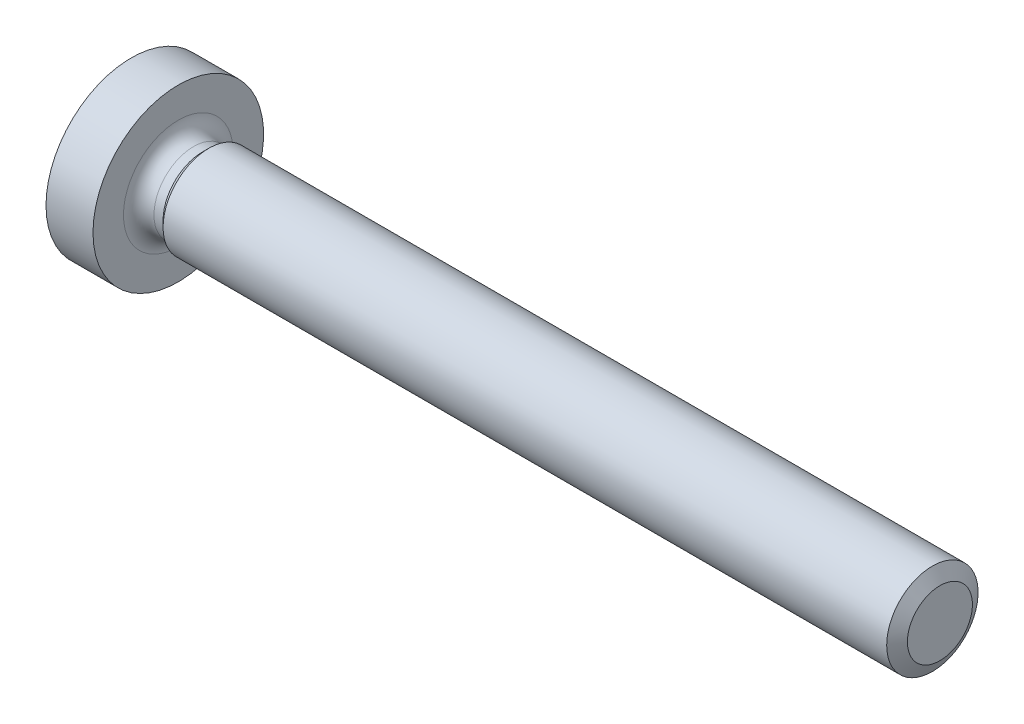
SolidWorks part; units mm, degrees
revolve "基体-旋转" add sketch "草图2" angle 360 about L0
sketch "草图2" plane through (0, 0, 0) normal (0, 0, 1) x (1, 0, 0)
  line L0 (-1.3318, 0) -> (6.5885, 0) construction
  line L1 (0, 0) -> (27.4, 0)
  line L2 (27.4, 0) -> (27.4, 1.5)
  line L3 (27.4, 1.5) -> (3.4, 1.5)
  line L4 (3.4, 1.5) -> (3.199, 1.299)
  line L5 (3.199, 1.299) -> (2.901, 1.299)
  line L6 (2.4, 1.8) -> (2.4, 2.8)
  line L7 (2.4, 2.8) -> (0.8575, 2.8)
  arc A0 (2.4, 1.8) -> (2.901, 1.299) centre (2.901, 1.8) ccw
  arc A1 (0, 0) -> (0.8575, 2.8) centre (5, 0) cw
  dimension "D3" = 5
  dimension "dk" = 5.6
  dimension "d" = 3
  dimension "l" = 25
  dimension "a" = 1
  dimension "D1" = 45
  dimension "D2" = 2.598
  dimension "da" = 3.6
  dimension "k" = 2.4
cosmetic thread "装饰螺纹线1" parameters "D1"=24, "D2"=2.598
ref_plane "前视" through (0, 0, 0) normal (0, 0, 1) x (1, 0, 0)
ref_plane "上视" through (0, 0, 0) normal (0, 1, 0) x (1, 0, 0)
ref_plane "右视" through (0, 0, 0) normal (1, 0, 0) x (0, 0, -1)
sketch "尺寸草图" plane through (0, 0, 0) normal (0, 0, 1) x (1, 0, 0)
  line L0 (0, 0) -> (25, 0)
  line L1 (0, 0) -> (0, 5.6)
  line L2 (25, 0) -> (25, 3.6)
  point P5 (0, 3)
  point P6 (24.5, 0)
  point P7 (1, 0)
  point P8 (2.4, 0)
  point P9 (20, 0)
  point P10 (3, 0)
  point P11 (23.2, 0)
  dimension "dk" = 5.6
  dimension "d" = 3
  dimension "l" = 25
  dimension "a" = 1
  dimension "da" = 3.6
  dimension "k" = 2.4
  dimension "P" = 0.5
  dimension "rf" = 5
  dimension "m" = 3
  dimension "h" = 1.8
sketch "草图3" plane through (0, 0, 0) normal (0, 0, 1) x (1, 0, 0)
  line L0 (27.1527, 1.5) -> (27.6527, 1.5)
  line L1 (27.6527, 1.5) -> (27.4, 1.067)
  line L2 (27.4, 1.067) -> (27.1527, 1.5)
  line L3 (27.4, 1.5) -> (3.4, 1.5) construction
  line L4 (27.4, -1.5) -> (27.4, 1.5) construction
  line L5 (-0.2428, 0) -> (7.1644, 0) construction
  line L6 (-1.3318, 0) -> (6.5885, 0) construction
  dimension "P" = 0.5
  dimension "D1" = 0.433
  dimension "D2" = 60
revolve "切除-旋转1" cut sketch "草图3" angle 360 about L5
sketch "草图5" plane through (0, 0, 0) normal (1, 0, 0) x (0, 0, -1)
  line L1 (0.25, 1.5) -> (-0.25, 1.5)
  line L2 (0.25, 1.5) -> (0.25, -1.5)
  line L3 (0.25, -1.5) -> (-0.25, -1.5)
  line L4 (-0.25, 1.5) -> (-0.25, -1.5)
  point P4 (0.25, 0)
  point P5 (0, 1.5)
  dimension "m" = 3
  dimension "D1" = 0.5
ref_plane "基准面1" through (1.8, 0, 0) normal (1, 0, 0) x (0, 0, -1)
pattern_linear "阵列(线性)1" [suppressed] count 49 spacing 0.5 along (1, 0, 0)
sketch "草图6" plane through (1.8, 0, 0) normal (1, 0, 0) x (0, 0, -1)
  point P0 (0, 0)
loft "切除-放样1" cut profiles "草图6", "草图5"
ref_plane "基准面2" through (0, 0, 0) normal (0, -0.7071, 0.7071) x (1, 0, 0)
mirror "镜向1" about plane through (0, 0, 0) normal (0, -0.7071, 0.7071) of "切除-放样1"
equation "\"l@草图2\" = \"l@尺寸草图\""
equation "\"dk@草图2\" = \"dk@尺寸草图\""
equation "\"k@草图2\" = \"k@尺寸草图\""
equation "\"D2@草图2\" = \"d@尺寸草图\"*0.866"
equation "\"a@草图2\" = \"a@尺寸草图\""
equation "\"D3@草图2\" = \"rf@尺寸草图\""
equation "\"d@草图2\" = \"d@尺寸草图\""
equation "\"da@草图2\" = \"da@尺寸草图\""
equation "\"D2@装饰螺纹线1\" = \"d@尺寸草图\"*0.866"
equation "\"D1@装饰螺纹线1\" = \"l@尺寸草图\"-\"a@尺寸草图\""
equation "\"P@草图3\" = \"P@尺寸草图\""
equation "\"D1@草图3\" = \"P@尺寸草图\"*0.866"
equation "\"h@基准面1\" = \"h@尺寸草图\""
equation "\"D1@草图5\" = \"P@尺寸草图\""
equation "\"m@草图5\" = \"m@尺寸草图\""
equation "\"D3@阵列(线性)1\" = \"P@尺寸草图\""
equation "\"D1@阵列(线性)1\" = (\"l@尺寸草图\"-\"a@尺寸草图\")/\"P@尺寸草图\"+1"
